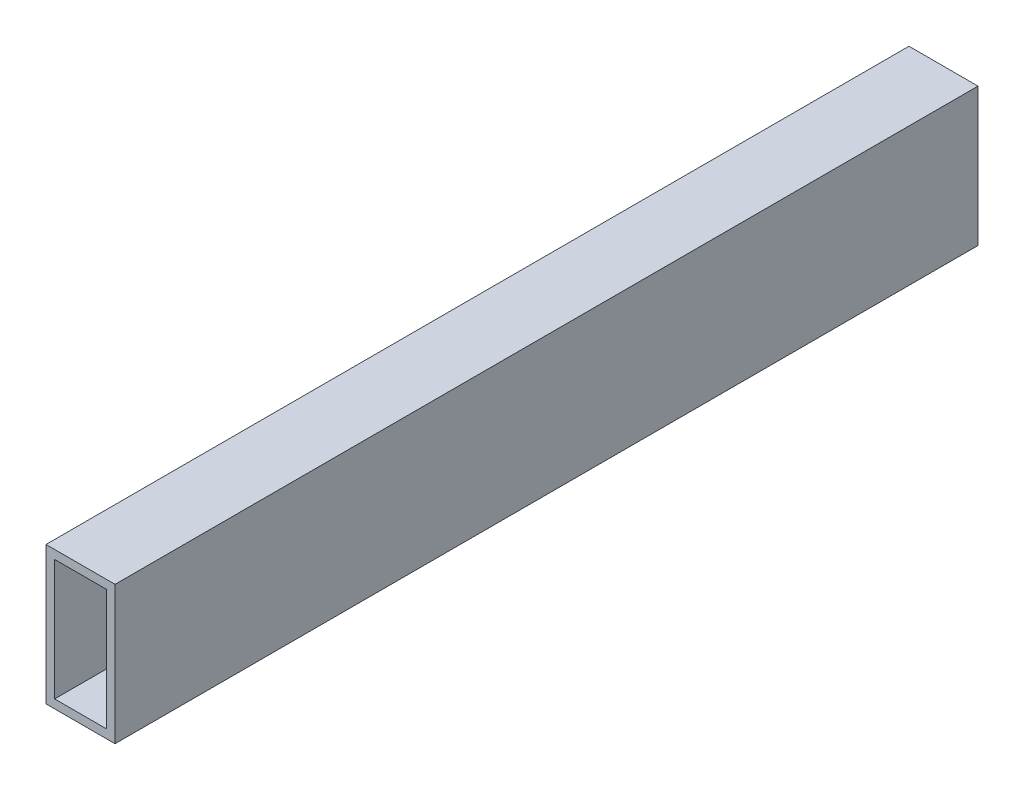
SolidWorks part; units mm, degrees
material "6061-T6 (SS)"
ref_plane "Front Plane" through (0, 0, 0) normal (0, 0, 1) x (1, 0, 0)
ref_plane "Top Plane" through (0, 0, 0) normal (0, 1, 0) x (1, 0, 0)
ref_plane "Right Plane" through (0, 0, 0) normal (1, 0, 0) x (0, 0, -1)
sketch "Sketch1" plane through (0, 0, 0) normal (0, 0, 1) x (1, 0, 0)
  line L1 (-12.7, -25.4) -> (12.7, -25.4)
  line L2 (-12.7, -25.4) -> (-12.7, 25.4)
  line L3 (-12.7, 25.4) -> (12.7, 25.4)
  line L4 (12.7, -25.4) -> (12.7, 25.4)
  line L5 (0, 25.4) -> (0, -25.4) construction
  line L6 (-12.7, 0) -> (12.7, 0) construction
  line L7 (-9.525, -22.225) -> (9.525, -22.225)
  line L8 (-9.525, -22.225) -> (-9.525, 22.225)
  line L9 (-9.525, 22.225) -> (9.525, 22.225)
  line L10 (9.525, -22.225) -> (9.525, 22.225)
  line L11 (0, 22.225) -> (0, -22.225) construction
  line L12 (-9.525, 0) -> (9.525, 0) construction
  point P0 (0, 0)
  point P4 (0, 0)
  dimension "D1" = 25.4
  dimension "D2" = 50.8
  dimension "D3" = 3.175
  dimension "D4" = 3.175
extrude "Boss-Extrude1" add sketch "Sketch1" along normal mid plane 317.5
